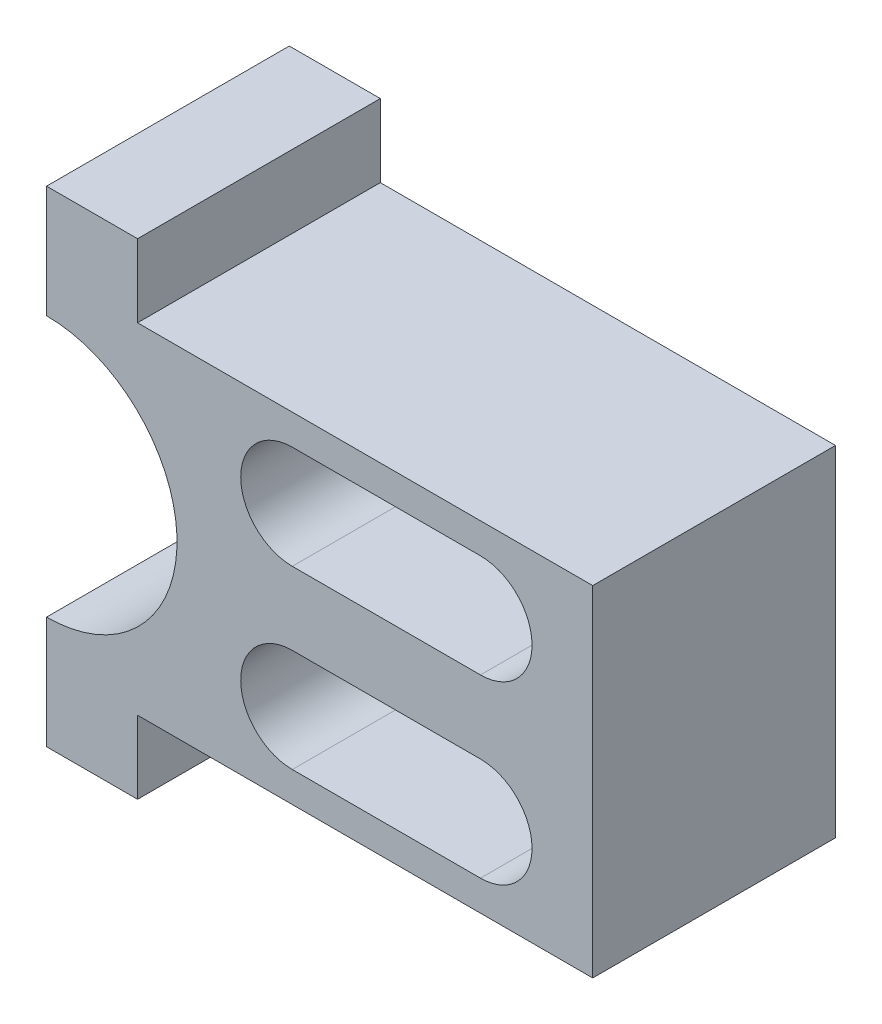
SolidWorks part; units mm, degrees
ref_plane "Спереди" through (0, 0, 0) normal (0, 0, 1) x (1, 0, 0)
ref_plane "Сверху" through (0, 0, 0) normal (0, 1, 0) x (1, 0, 0)
ref_plane "Справа" through (0, 0, 0) normal (1, 0, 0) x (0, 0, -1)
other "Configuration Table"
sketch "Эскиз1" plane through (0, 0, 0) normal (0, 0, 1) x (1, 0, 0)
  line L0 (-99.3893, 0) -> (98.5032, 0) construction
  line L1 (45, 40) -> (-45, 40)
  line L2 (45, 40) -> (45, -40)
  line L3 (45, -40) -> (-45, -40)
  line L4 (-45, 40) -> (-45, -40)
  line L5 (45, 40) -> (-45, -40) construction
  line L6 (45, -40) -> (-45, 40) construction
  line L7 (-4.5, -14.5) -> (26.5, -14.5) construction
  line L8 (-4.5, -6) -> (26.5, -6)
  line L9 (-4.5, -23) -> (26.5, -23)
  line L10 (-4.5, 14.5) -> (26.5, 14.5) construction
  line L11 (-4.5, 6) -> (26.5, 6)
  line L12 (-4.5, 23) -> (26.5, 23)
  arc A0 (-45, -21.5) -> (-45, 21.5) centre (-45, 0) ccw
  arc A1 (-4.5, -6) -> (-4.5, -23) centre (-4.5, -14.5) ccw
  arc A2 (26.5, -23) -> (26.5, -6) centre (26.5, -14.5) ccw
  arc A3 (-4.5, 6) -> (-4.5, 23) centre (-4.5, 14.5) cw
  arc A4 (26.5, 23) -> (26.5, 6) centre (26.5, 14.5) cw
  point P0 (0, 0)
  point P13 (11, -14.5)
  point P18 (35, -14.5)
  point P21 (11, 14.5)
  dimension "D3" = 43
  dimension "D1" = 80
  dimension "D2" = 90
  dimension "D4" = 17
  dimension "D5" = 48
  dimension "D6" = 6
  dimension "D7" = 10
extrude "Бобышка-Вытянуть1" add sketch "Эскиз1" along normal blind 40 contours A0 L4 L3 L2 L1 A2 L9 A1 L8 L12 A4 L11 A3
sketch "Эскиз2" plane through (0, 0, 40) normal (0, 0, 1) x (1, 0, 0)
  line L0 (-45, 40) -> (-45, 21.5) construction
  line L1 (45, 40) -> (-30, 40)
  line L2 (45, 40) -> (45, 28)
  line L3 (45, 28) -> (-30, 28)
  line L4 (-30, 40) -> (-30, 28)
  dimension "D1" = 12
  dimension "D2" = 15
extrude "Вырез-Вытянуть1" cut sketch "Эскиз2" against normal through all
mirror "Зеркальное отражение1" about plane through (0, 0, 0) normal (0, 1, 0) of "Вырез-Вытянуть1"
